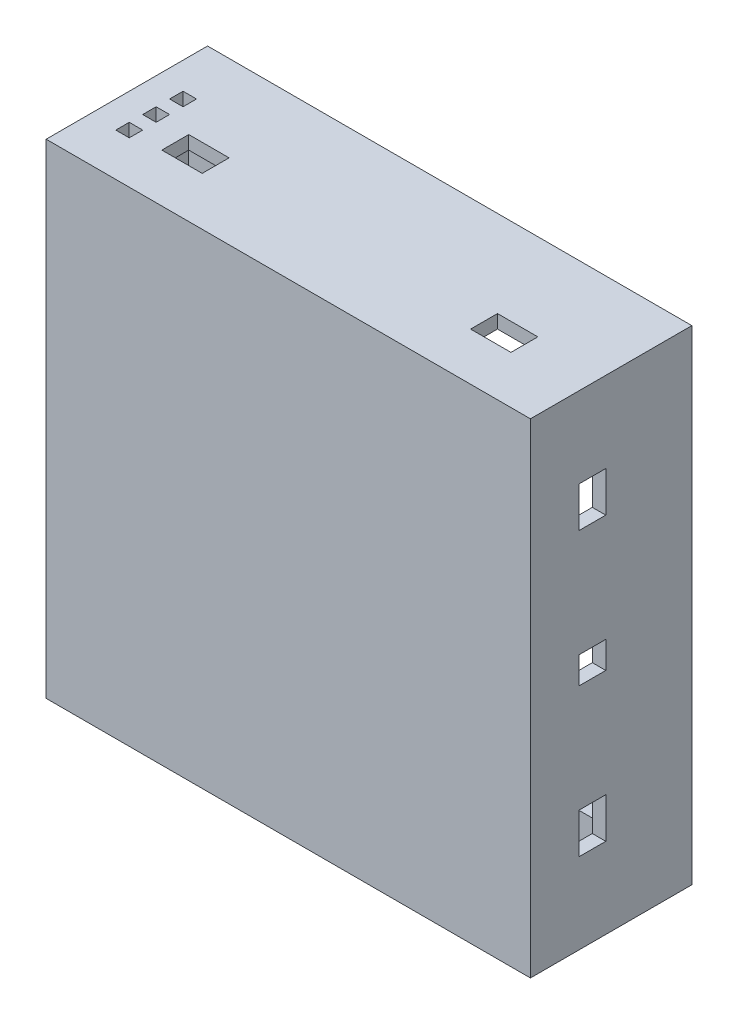
SolidWorks part; units mm, degrees
ref_plane "Front Plane" through (0, 0, 0) normal (0, 0, 1) x (1, 0, 0)
ref_plane "Top Plane" through (0, 0, 0) normal (0, 1, 0) x (1, 0, 0)
ref_plane "Right Plane" through (0, 0, 0) normal (1, 0, 0) x (0, 0, -1)
sketch "Sketch1" plane through (0, 0, 0) normal (0, 0, 1) x (1, 0, 0)
  line L1 (0, 0) -> (180, 0)
  line L2 (0, 0) -> (0, 180)
  line L3 (0, 180) -> (180, 180)
  line L4 (180, 0) -> (180, 180)
  dimension "D1" = 180
  dimension "D2" = 180
extrude "Boss-Extrude1" add sketch "Sketch1" along normal blind 10
sketch "Sketch2" plane through (0, 0, 10) normal (0, 0, 1) x (1, 0, 0)
  line L0 (0, 180) -> (0, 0) construction
  line L1 (10, 10) -> (170, 10)
  line L2 (10, 10) -> (10, 170)
  line L3 (10, 170) -> (170, 170)
  line L4 (170, 10) -> (170, 170)
  line L5 (180, 0) -> (180, 180) construction
  line L6 (180, 180) -> (0, 180) construction
  line L7 (0, 0) -> (180, 0) construction
  line L9 (0, 0) -> (180, 0)
  line L10 (0, 0) -> (0, 180)
  line L11 (0, 180) -> (180, 180)
  line L12 (180, 0) -> (180, 180)
  dimension "D1" = 10
  dimension "D2" = 10
  dimension "D3" = 10
  dimension "D4" = 10
extrude "Boss-Extrude2" add sketch "Sketch2" along normal blind 80
sketch "Sketch3" plane through (0, 0, 10) normal (0, 0, 1) x (1, 0, 0)
  line L0 (170, 10) -> (170, 170) construction
  line L1 (10, 10) -> (170, 10)
  line L2 (10, 10) -> (10, 30)
  line L3 (10, 30) -> (170, 30)
  line L4 (170, 10) -> (170, 30)
  line L5 (170, 10) -> (170, 170) construction
  line L6 (10, 170) -> (170, 170)
  line L7 (10, 170) -> (10, 150)
  line L8 (10, 150) -> (170, 150)
  line L9 (170, 170) -> (170, 150)
  dimension "D1" = 20
  dimension "D2" = 20
extrude "Boss-Extrude4" add sketch "Sketch3" along normal blind 20
sketch "Sketch5" plane through (180, 0, 0) normal (1, 0, 0) x (0, 0, -1)
  line L0 (-90, 0) -> (0, 0) construction
  line L1 (-90, 180) -> (-70, 180)
  line L2 (-90, 180) -> (-90, 0)
  line L3 (-90, 0) -> (-70, 0)
  line L4 (-70, 180) -> (-70, 0)
  dimension "D1" = 20
extrude "Cut-Extrude1" cut sketch "Sketch5" against normal blind 300 contours L2 L1 L4 L3
sketch "Sketch6" plane through (0, 0, 30) normal (0, 0, 1) x (1, 0, 0)
  line L0 (170, 10) -> (170, 170) construction
  line L1 (10, 170) -> (170, 170)
  line L2 (10, 170) -> (10, 150)
  line L3 (10, 150) -> (170, 150)
  line L4 (170, 170) -> (170, 150)
  line L5 (170, 30) -> (170, 150) construction
  line L7 (10, 30) -> (170, 30)
  line L8 (10, 30) -> (10, 10)
  line L9 (10, 10) -> (170, 10)
  line L10 (170, 30) -> (170, 10)
extrude "Cut-Extrude2" cut sketch "Sketch6" against normal blind 5
ref_plane "Plane1" through (0, 0, 62) normal (0, 0, 1) x (1, 0, 0)
sketch "Sketch9" plane through (0, 0, 62) normal (0, 0, 1) x (1, 0, 0)
  line L5 (170, 10) -> (170, 170) construction
  line L6 (10, 10) -> (170, 10)
  line L7 (10, 10) -> (10, 25)
  line L8 (10, 25) -> (170, 25)
  line L9 (170, 10) -> (170, 25)
  line L11 (10, 170) -> (170, 170)
  line L12 (10, 170) -> (10, 155)
  line L13 (10, 155) -> (170, 155)
  line L14 (170, 170) -> (170, 155)
  dimension "D1" = 15
  dimension "D2" = 15
extrude "Boss-Extrude6" add sketch "Sketch9" against normal blind 10
sketch "Sketch11" plane through (0, 0, 0) normal (-1, 0, 0) x (0, 0, 1)
  line L0 (0, 180) -> (0, 0) construction
  line L1 (20, 122) -> (48, 122)
  line L2 (20, 122) -> (20, 45)
  line L3 (20, 45) -> (48, 45)
  line L4 (48, 122) -> (48, 45)
  line L5 (70, 0) -> (0, 0) construction
  dimension "D1" = 77
  dimension "D2" = 28
  dimension "D3" = 20
  dimension "D4" = 45
extrude "Cut-Extrude4" cut sketch "Sketch11" against normal blind 10
sketch "Sketch12" plane through (170, 0, 0) normal (-1, 0, 0) x (0, 0, 1)
  line L0 (25.8804, 149.8073) -> (25.8804, 0)
  line L1 (70, 0) -> (0, 0) construction
sketch "Sketch13" plane through (180, 0, 0) normal (1, 0, 0) x (0, 0, -1)
  line L0 (-70, 0) -> (0, 0) construction
  line L1 (-50.27, 30) -> (-40.27, 30)
  line L2 (-50.27, 30) -> (-50.27, 40)
  line L3 (-50.27, 40) -> (-40.27, 40)
  line L4 (-40.27, 30) -> (-40.27, 40)
  line L5 (-70, 180) -> (0, 180) construction
  line L6 (-50.27, 140) -> (-40.27, 140)
  line L7 (-50.27, 140) -> (-50.27, 150)
  line L8 (-50.27, 150) -> (-40.27, 150)
  line L9 (-40.27, 140) -> (-40.27, 150)
  line L11 (-50.27, 95) -> (-40.27, 95)
  line L12 (-50.27, 95) -> (-50.27, 85)
  line L13 (-50.27, 85) -> (-40.27, 85)
  line L14 (-40.27, 95) -> (-40.27, 85)
  point P16 (-45.27, 85)
  dimension "D1" = 10
  dimension "D2" = 30
  dimension "D3" = 10
  dimension "D4" = 10
  dimension "D5" = 30
  dimension "D6" = 10
  dimension "D7" = 10
  dimension "D8" = 45
extrude "Cut-Extrude5" cut sketch "Sketch13" against normal blind 10
sketch "Sketch15" plane through (0, 0, 70) normal (0, 0, 1) x (1, 0, 0)
  line L0 (170, 149.8073) -> (170, 0) construction
  line L1 (180, 180) -> (170, 180)
  line L2 (180, 180) -> (180, 0)
  line L3 (180, 0) -> (170, 0)
  line L4 (170, 180) -> (170, 0)
  line L5 (0, 0) -> (180, 0) construction
extrude "Boss-Extrude7" add sketch "Sketch15" against normal blind 30
sketch "Sketch16" plane through (180, 0, 0) normal (1, 0, 0) x (0, 0, -1)
  line L0 (-70, 0) -> (0, 0) construction
  line L1 (-50, 30) -> (-40, 30)
  line L2 (-50, 30) -> (-50, 45)
  line L3 (-50, 45) -> (-40, 45)
  line L4 (-40, 30) -> (-40, 45)
  line L5 (-70, 180) -> (-70, 0) construction
  line L6 (-70, 180) -> (0, 180) construction
  line L7 (-40, 82.5) -> (-50, 82.5)
  line L8 (-40, 82.5) -> (-40, 97.5)
  line L9 (-40, 97.5) -> (-50, 97.5)
  line L10 (-50, 82.5) -> (-50, 97.5)
  line L11 (-40, 135) -> (-50, 135)
  line L12 (-40, 135) -> (-40, 150)
  line L13 (-40, 150) -> (-50, 150)
  line L14 (-50, 135) -> (-50, 150)
  dimension "D1" = 15
  dimension "D2" = 10
  dimension "D3" = 30
  dimension "D4" = 20
  dimension "D5" = 15
  dimension "D6" = 15
  dimension "D7" = 30
  dimension "D8" = 37.5
extrude "Cut-Extrude6" cut sketch "Sketch16" against normal blind 30
sketch "Sketch17" plane through (0, 180, 0) normal (0, 1, 0) x (1, 0, 0)
  line L0 (0, -70) -> (0, 0) construction
  line L1 (20, -50) -> (30, -50)
  line L2 (20, -50) -> (20, -40)
  line L3 (20, -40) -> (30, -40)
  line L4 (30, -50) -> (30, -40)
  line L5 (0, -70) -> (180, -70) construction
  line L6 (180, -70) -> (180, 0) construction
  line L7 (150, -40) -> (160, -40)
  line L8 (150, -40) -> (150, -50)
  line L9 (150, -50) -> (160, -50)
  line L10 (160, -40) -> (160, -50)
  dimension "D1" = 10
  dimension "D2" = 10
  dimension "D3" = 20
  dimension "D4" = 20
  dimension "D5" = 10
  dimension "D6" = 20
extrude "Cut-Extrude7" cut sketch "Sketch17" against normal blind 300
sketch "Sketch22" plane through (180, 0, 0) normal (1, 0, 0) x (0, 0, -1)
  line L1 (-34.8962, 75.9242) -> (-54.9658, 75.9242)
  line L2 (-34.8962, 75.9242) -> (-34.8962, 105.2183)
  line L3 (-34.8962, 105.2183) -> (-54.9658, 105.2183)
  line L4 (-54.9658, 75.9242) -> (-54.9658, 105.2183)
extrude "Boss-Extrude8" add sketch "Sketch22" against normal blind 10
sketch "Sketch23" plane through (0, 0, 0) normal (0, -1, 0) x (1, 0, 0)
  line L0 (30, 40) -> (20, 40) construction
  line L1 (20, 30) -> (30, 30)
  line L2 (20, 30) -> (20, 20)
  line L3 (20, 20) -> (30, 20)
  line L4 (30, 30) -> (30, 20)
  dimension "D1" = 10
  dimension "D2" = 10
  dimension "D3" = 10
extrude "Cut-Extrude11" cut sketch "Sketch23" against normal blind 10
sketch "Sketch24" plane through (0, 180, 0) normal (0, 1, 0) x (1, 0, 0)
  line L0 (180, -70) -> (180, 0) construction
  line L1 (0, 0) -> (180, 0)
  line L2 (0, 0) -> (0, -30)
  line L3 (0, -30) -> (180, -30)
  line L4 (180, 0) -> (180, -30)
  dimension "D1" = 30
extrude "Cut-Extrude12" cut sketch "Sketch24" against normal blind 300
sketch "Sketch26" plane through (0, 0, 0) normal (-1, 0, 0) x (0, 0, 1)
  line L1 (30, 122) -> (48, 122)
  line L2 (30, 122) -> (30, 45)
  line L3 (30, 45) -> (48, 45)
  line L4 (48, 122) -> (48, 45)
extrude "Boss-Extrude9" add sketch "Sketch26" against normal blind 10
sketch "Sketch27" plane through (0, 0, 62) normal (0, 0, 1) x (1, 0, 0)
  line L1 (10, 170) -> (170, 170)
  line L2 (10, 170) -> (10, 10)
  line L3 (10, 10) -> (170, 10)
  line L4 (170, 170) -> (170, 10)
extrude "Cut-Extrude13" cut sketch "Sketch27" against normal blind 10
sketch "Sketch28" plane through (0, 180, 0) normal (0, 1, 0) x (1, 0, 0)
  line L0 (180, -70) -> (180, -30) construction
  line L1 (0, -70) -> (180, -70)
  line L2 (0, -70) -> (0, -62.5)
  line L3 (0, -62.5) -> (180, -62.5)
  line L4 (180, -70) -> (180, -62.5)
  dimension "D1" = 7.5
extrude "Boss-Extrude10" add sketch "Sketch28" against normal blind 180
sketch "Sketch29" plane through (0, 0, 62.5) normal (0, 0, -1) x (-1, 0, 0)
  line L0 (-10, 10) -> (-10, 170) construction
  line L1 (-170, 170) -> (-10, 170)
  line L2 (-170, 170) -> (-170, 160)
  line L3 (-170, 160) -> (-10, 160)
  line L4 (-10, 170) -> (-10, 160)
  line L5 (-10, 90) -> (-48.3428, 90)
  line L6 (-10, 170) -> (-10, 10) construction
  line L7 (-170, 20) -> (-10, 20)
  line L8 (-10, 10) -> (-10, 20)
  line L9 (-170, 10) -> (-10, 10)
  line L10 (-170, 10) -> (-170, 20)
  line M6 (-170, 170) -> (-170, 10)
  line M7 (-170, 10) -> (-10, 10)
  line M8 (-10, 10) -> (-10, 170)
  line M9 (-10, 170) -> (-170, 170)
  dimension "D1" = 10
extrude "Boss-Extrude11" add sketch "Sketch29" along normal blind 5 contours L3 M6 M8 M9 | L7 M6 M7 M8
sketch "Sketch34" plane through (0, 0, 30) normal (0, 0, -1) x (-1, 0, 0)
  line L0 (-180, 0) -> (-180, 180) construction
  line L1 (-175, 175) -> (-5, 175)
  line L2 (-175, 175) -> (-175, 5)
  line L3 (-175, 5) -> (-5, 5)
  line L4 (-5, 175) -> (-5, 5)
  line L5 (0, 0) -> (0, 180) construction
  line L6 (0, 180) -> (-180, 180) construction
  line L7 (-180, 0) -> (0, 0) construction
  dimension "D1" = 5
  dimension "D2" = 5
  dimension "D3" = 5
  dimension "D4" = 5
extrude "Cut-Extrude14" cut sketch "Sketch34" against normal blind 40
sketch "Sketch35" plane through (0, 0, 70) normal (0, 0, 1) x (1, 0, 0)
  line L1 (0, 180) -> (180, 180)
  line L2 (0, 180) -> (0, 0)
  line L3 (0, 0) -> (180, 0)
  line L4 (180, 180) -> (180, 0)
  line L5 (5, 175) -> (175, 175)
  line L6 (5, 175) -> (5, 5)
  line L7 (5, 5) -> (175, 5)
  line L8 (175, 175) -> (175, 5)
extrude "Boss-Extrude13" add sketch "Sketch35" along normal blind 20
sketch "Sketch36" plane through (0, 0, 0) normal (0, -1, 0) x (1, 0, 0)
  line L0 (180, 90) -> (180, 30) construction
  line L1 (0, 90) -> (180, 90)
  line L2 (0, 90) -> (0, 85)
  line L3 (0, 85) -> (180, 85)
  line L4 (180, 90) -> (180, 85)
  dimension "D1" = 5
extrude "Boss-Extrude14" add sketch "Sketch36" against normal blind 180
sketch "Sketch37" plane through (0, 0, 30) normal (0, 0, -1) x (-1, 0, 0)
  line L1 (-180, 180) -> (0, 180)
  line L2 (-180, 180) -> (-180, 0)
  line L3 (-180, 0) -> (0, 0)
  line L4 (0, 180) -> (0, 0)
  line L5 (-175, 175) -> (-5, 175)
  line L6 (-175, 175) -> (-175, 5)
  line L7 (-175, 5) -> (-5, 5)
  line L8 (-5, 175) -> (-5, 5)
extrude "Boss-Extrude15" add sketch "Sketch37" against normal blind 40
sketch "Sketch38" plane through (0, 0, 85) normal (0, 0, -1) x (-1, 0, 0)
  line L0 (-5, 5) -> (-5, 175) construction
  line L1 (-175, 175) -> (-5, 175)
  line L2 (-175, 175) -> (-175, 160)
  line L3 (-175, 160) -> (-5, 160)
  line L4 (-5, 175) -> (-5, 160)
  line L6 (-175, 5) -> (-5, 5)
  line L7 (-175, 5) -> (-175, 20)
  line L8 (-175, 20) -> (-5, 20)
  line L9 (-5, 5) -> (-5, 20)
  dimension "D1" = 15
  dimension "D2" = 15
extrude "Boss-Extrude16" add sketch "Sketch38" along normal blind 5
sketch "Sketch39" plane through (180, 0, 0) normal (1, 0, 0) x (0, 0, -1)
  line L0 (-90, 180) -> (-30, 180) construction
  line L1 (-72, 150) -> (-62, 150)
  line L2 (-72, 150) -> (-72, 135)
  line L3 (-72, 135) -> (-62, 135)
  line L4 (-62, 150) -> (-62, 135)
  line L5 (-90, 0) -> (-90, 180) construction
  line L6 (-90, 0) -> (-30, 0) construction
  line L7 (-72, 45) -> (-62, 45)
  line L8 (-72, 45) -> (-72, 30)
  line L9 (-72, 30) -> (-62, 30)
  line L10 (-62, 45) -> (-62, 30)
  line L12 (-72, 95) -> (-62, 95)
  line L13 (-72, 95) -> (-72, 85)
  line L14 (-72, 85) -> (-62, 85)
  line L15 (-62, 95) -> (-62, 85)
  dimension "D1" = 15
  dimension "D2" = 10
  dimension "D3" = 30
  dimension "D4" = 18
  dimension "D5" = 15
  dimension "D6" = 30
  dimension "D7" = 10
  dimension "D8" = 40
extrude "Cut-Extrude15" cut sketch "Sketch39" against normal blind 5
sketch "Sketch40" plane through (0, 180, 0) normal (0, 1, 0) x (1, 0, 0)
  line L0 (180, -90) -> (0, -90) construction
  line L1 (25, -62) -> (40, -62)
  line L2 (25, -62) -> (25, -72)
  line L3 (25, -72) -> (40, -72)
  line L4 (40, -62) -> (40, -72)
  line L5 (0, -90) -> (0, -30) construction
  dimension "D1" = 18
  dimension "D2" = 10
  dimension "D3" = 15
  dimension "D4" = 25
extrude "Cut-Extrude16" cut sketch "Sketch40" against normal blind 300
sketch "Sketch42" plane through (0, 180, 0) normal (0, 1, 0) x (1, 0, 0)
  line L0 (90, -30) -> (90, -85)
  line L1 (0, -30) -> (180, -30) construction
  line L2 (90, -30) -> (90, -37)
  dimension "D1" = 55
  dimension "D2" = 7
ref_plane "Plane3" through (0, 0, 37) normal (0, 0, -1) x (-1, 0, 0)
sketch "Sketch44" plane through (0, 0, 37) normal (0, 0, -1) x (-1, 0, 0)
  line L1 (-175, 175) -> (-5, 175)
  line L2 (-175, 175) -> (-175, 5)
  line L3 (-175, 5) -> (-5, 5)
  line L4 (-5, 175) -> (-5, 5)
  line L5 (-165, 165) -> (-15, 165)
  line L6 (-165, 165) -> (-165, 15)
  line L7 (-165, 15) -> (-15, 15)
  line L8 (-15, 165) -> (-15, 15)
  dimension "D1" = 10
  dimension "D2" = 10
  dimension "D3" = 10
  dimension "D4" = 10
extrude "Boss-Extrude17" add sketch "Sketch44" against normal blind 5
sketch "Sketch45" plane through (0, 180, 0) normal (0, 1, 0) x (1, 0, 0)
  line L0 (0, -90) -> (0, -30) construction
  line L1 (10, -64.1145) -> (15, -64.1145)
  line L2 (10, -64.1145) -> (10, -59.1145)
  line L3 (10, -59.1145) -> (15, -59.1145)
  line L4 (15, -64.1145) -> (15, -59.1145)
  line L5 (10, -54.1145) -> (15, -54.1145)
  line L6 (10, -54.1145) -> (10, -49.1145)
  line L7 (10, -49.1145) -> (15, -49.1145)
  line L8 (15, -54.1145) -> (15, -49.1145)
  line L10 (10, -69.1145) -> (15, -69.1145)
  line L11 (10, -69.1145) -> (10, -74.1145)
  line L12 (10, -74.1145) -> (15, -74.1145)
  line L13 (15, -69.1145) -> (15, -74.1145)
  point P14 (12.5, -69.1145)
  dimension "D1" = 10
  dimension "D2" = 10
  dimension "D3" = 5
  dimension "D4" = 5
  dimension "D5" = 5
  dimension "D6" = 5
  dimension "D7" = 5
  dimension "D8" = 5
  dimension "D9" = 5
  dimension "D10" = 5
extrude "Cut-Extrude17" cut sketch "Sketch45" against normal blind 5
sketch "Sketch46" plane through (0, 180, 0) normal (0, 1, 0) x (1, 0, 0)
  line L1 (140, -62.2417) -> (155, -62.2417)
  line L2 (140, -62.2417) -> (140, -72.2417)
  line L3 (140, -72.2417) -> (155, -72.2417)
  line L4 (155, -62.2417) -> (155, -72.2417)
  line L7 (25, -62) -> (25, -72)
  line L9 (180, -90) -> (180, -30) construction
  dimension "D1" = 10
  dimension "D2" = 15
  dimension "D3" = 25
extrude "Cut-Extrude18" cut sketch "Sketch46" against normal blind 300 contours L4 L1 L2 L3
equation "\"ๅจ\"=300"
